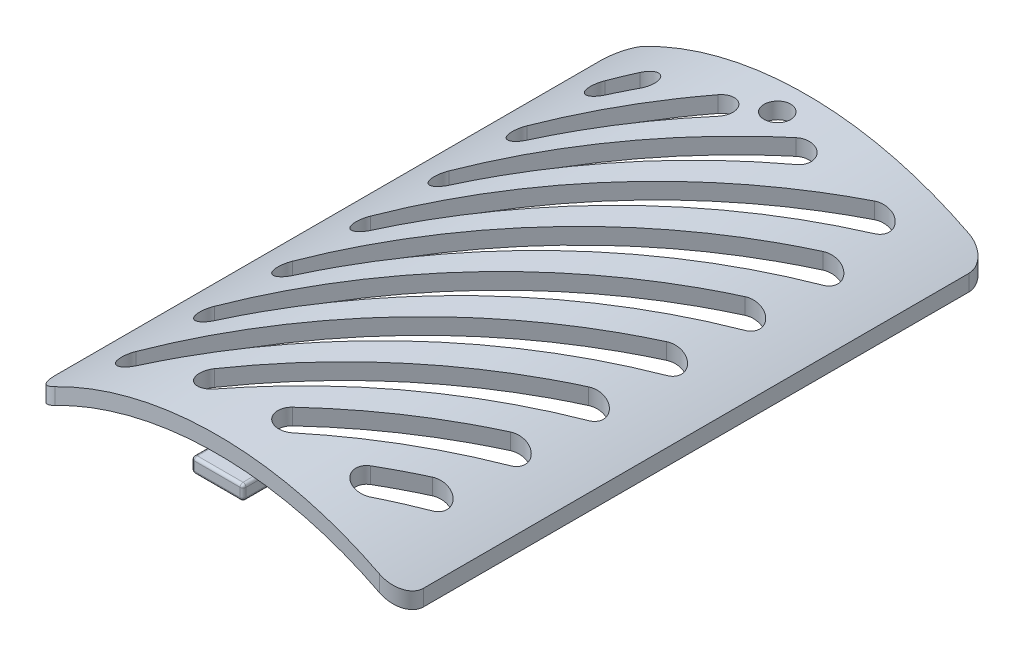
SolidWorks part; units mm, degrees
ref_plane "Plan de face" through (0, 0, 0) normal (0, 0, 1) x (1, 0, 0)
ref_plane "Plan de dessus" through (0, 0, 0) normal (0, 1, 0) x (1, 0, 0)
ref_plane "Plan de droite" through (0, 0, 0) normal (1, 0, 0) x (0, 0, -1)
sketch "Esquisse2" plane through (0, 0, 0) normal (0, 0, 1) x (1, 0, 0)
  line L1 (-25, 0) -> (25, 0) construction
  line L2 (-25, 0) -> (-25, 2.2)
  line L3 (25, 0) -> (25, 2.2)
  line L4 (0, 9.2) -> (0, 7) construction
  arc A0 (-25, 0) -> (25, 0) centre (0, -41.1429) cw
  arc A1 (-25, 2.2) -> (25, 2.2) centre (0, -38.9429) cw
  point P4 (0, 0)
  point P6 (0, 7)
  dimension "D1" = 50
  dimension "D2" = 7
  dimension "D3" = 2.2
extrude "Boss.-Extru.1" add sketch "Esquisse2" along normal blind 80
sketch "Esquisse3" plane through (0, 0, 0) normal (1, 0, 0) x (0, 0, -1)
  line L0 (-77.9, 7) -> (-77.9, 5)
  line L2 (-77.9, 5) -> (-80, 5)
  line L3 (-80, 5) -> (-80, 3)
  line L6 (-73.9, 7) -> (-77.9, 7)
  line L7 (-77.9, 7) -> (-77.9, 9.2) construction
  line L8 (-80, 3) -> (-75.9, 3)
  line L9 (-75.9, 3) -> (-73.9, 5)
  line L10 (-73.9, 5) -> (-73.9, 7)
  line L11 (-77.9, 9.2) -> (-80, 9.2) construction
  dimension "D1" = 2.1
  dimension "D2" = 2
  dimension "D3" = 4
  dimension "D4" = 2
  dimension "D5" = 2.2
  dimension "D6" = 135
  dimension "D7" = 2.1
extrude "Boss.-Extru.2" add sketch "Esquisse3" along normal mid plane 7
ref_plane "Plan1" through (0, 9.2, 0) normal (0, 1, 0) x (1, 0, 0)
hole_wizard "Dégagement M31" positions "Esquisse7" profile "Esquisse8" hole size "M3" standard "ISO"
sketch "Esquisse7" plane through (0, 9.2, 0) normal (0, 1, 0) x (1, 0, 0)
  line L0 (25, 0) -> (-25, 0) construction
  line L1 (0, -4) -> (0, 0) construction
  point P0 (0, -4)
  dimension "D1" = 4
sketch "Esquisse8" plane through (0, 9.2, 4) normal (1, 0, 0) x (0, 0, 1)
  line L0 (0, 0) -> (0, 11.0815)
  line L1 (0, 11.0815) -> (1.8, 10)
  line L2 (1.8, 10) -> (1.8, 0)
  line L5 (1.8, 0) -> (0, 0)
  line L10 (0, 11.0815) -> (-1.8, 10) construction
  line L11 (0, -6.35) -> (0, 107.95) construction
  dimension "Diamètre du perçage" = 3.6
  dimension "Profondeur du perçage" = 10
  dimension "Angle de pointe" = 118
fillet "Congé1" radius 3 4 edges at (25, 1.1, 0) (25, 1.1, 80) (-25, 1.1, 0) (-25, 1.1, 80)
sketch "Esquisse9" plane through (0, 9.2, 0) normal (0, 1, 0) x (1, 0, 0)
  line L0 (-18, -73) -> (18, -37) construction
  line L1 (-19.4142, -71.5858) -> (16.5858, -35.5858)
  line L2 (-16.5858, -74.4142) -> (19.4142, -38.4142)
  line L3 (-18, -62.3934) -> (18, -26.3934) construction
  line L4 (-19.4142, -60.9792) -> (16.5858, -24.9792)
  line L5 (-16.5858, -63.8076) -> (19.4142, -27.8076)
  line L6 (-18, -51.7868) -> (18, -15.7868) construction
  line L7 (-19.4142, -50.3726) -> (16.5858, -14.3726)
  line L8 (-16.5858, -53.201) -> (19.4142, -17.201)
  line L9 (-18, -41.1802) -> (16.1802, -7) construction
  line L10 (-19.4142, -39.766) -> (14.766, -5.5858)
  line L11 (-16.5858, -42.5944) -> (17.5944, -8.4142)
  line L12 (-22, -80) -> (22, -80) construction
  line L13 (-25, -77) -> (-25, -3) construction
  line L14 (25, -77) -> (25, -3) construction
  line L15 (-7.3934, -73) -> (18, -47.6066) construction
  line L16 (-8.8076, -71.5858) -> (16.5858, -46.1924)
  line L17 (-5.9792, -74.4142) -> (19.4142, -49.0208)
  line L18 (3.2132, -73) -> (18, -58.2132) construction
  line L19 (1.799, -71.5858) -> (16.5858, -56.799)
  line L20 (4.6274, -74.4142) -> (19.4142, -59.6274)
  line L21 (13.8198, -73) -> (18, -68.8198) construction
  line L22 (12.4056, -71.5858) -> (16.5858, -67.4056)
  line L23 (15.234, -74.4142) -> (19.4142, -70.234)
  line L24 (-18, -30.5736) -> (5.5736, -7) construction
  line L25 (-19.4142, -29.1594) -> (4.1594, -5.5858)
  line L26 (-16.5858, -31.9878) -> (6.9878, -8.4142)
  line L27 (-18, -19.967) -> (-5.033, -7) construction
  line L28 (-19.4142, -18.5528) -> (-6.4472, -5.5858)
  line L29 (-16.5858, -21.3812) -> (-3.6188, -8.4142)
  line L30 (-18, -9.3604) -> (-15.6396, -7) construction
  line L31 (-19.4142, -7.9462) -> (-17.0538, -5.5858)
  line L32 (-16.5858, -10.7746) -> (-14.2254, -8.4142)
  line L33 (22, 0) -> (-22, 0) construction
  arc A0 (-19.4142, -71.5858) -> (-16.5858, -74.4142) centre (-18, -73) ccw
  arc A5 (19.4142, -38.4142) -> (16.5858, -35.5858) centre (18, -37) ccw
  arc A6 (-19.4142, -60.9792) -> (-16.5858, -63.8076) centre (-18, -62.3934) ccw
  arc A7 (19.4142, -27.8076) -> (16.5858, -24.9792) centre (18, -26.3934) ccw
  arc A8 (-19.4142, -50.3726) -> (-16.5858, -53.201) centre (-18, -51.7868) ccw
  arc A9 (19.4142, -17.201) -> (16.5858, -14.3726) centre (18, -15.7868) ccw
  arc A10 (-19.4142, -39.766) -> (-16.5858, -42.5944) centre (-18, -41.1802) ccw
  arc A11 (17.5944, -8.4142) -> (14.766, -5.5858) centre (16.1802, -7) ccw
  arc A12 (-8.8076, -71.5858) -> (-5.9792, -74.4142) centre (-7.3934, -73) ccw
  arc A13 (19.4142, -49.0208) -> (16.5858, -46.1924) centre (18, -47.6066) ccw
  arc A14 (1.799, -71.5858) -> (4.6274, -74.4142) centre (3.2132, -73) ccw
  arc A15 (19.4142, -59.6274) -> (16.5858, -56.799) centre (18, -58.2132) ccw
  arc A16 (12.4056, -71.5858) -> (15.234, -74.4142) centre (13.8198, -73) ccw
  arc A17 (19.4142, -70.234) -> (16.5858, -67.4056) centre (18, -68.8198) ccw
  arc A18 (-19.4142, -29.1594) -> (-16.5858, -31.9878) centre (-18, -30.5736) ccw
  arc A19 (6.9878, -8.4142) -> (4.1594, -5.5858) centre (5.5736, -7) ccw
  arc A20 (-19.4142, -18.5528) -> (-16.5858, -21.3812) centre (-18, -19.967) ccw
  arc A21 (-3.6188, -8.4142) -> (-6.4472, -5.5858) centre (-5.033, -7) ccw
  arc A22 (-19.4142, -7.9462) -> (-16.5858, -10.7746) centre (-18, -9.3604) ccw
  arc A23 (-14.2254, -8.4142) -> (-17.0538, -5.5858) centre (-15.6396, -7) ccw
  point P2 (0, -55)
  point P7 (0, -44.3934)
  point P14 (0, -33.7868)
  point P21 (-0.9099, -24.0901)
  point P28 (5.3033, -60.3033)
  point P41 (10.6066, -65.6066)
  point P48 (15.9099, -70.9099)
  point P55 (-6.2132, -18.7868)
  point P62 (-11.5165, -13.4835)
  point P69 (-16.8198, -8.1802)
  point P76 (-3.2132, -5.1802)
  dimension "D1" = 2
  dimension "D2" = 7
  dimension "D3" = 7
  dimension "D4" = 7
  dimension "D5" = 45
  dimension "D6" = 7.5
  dimension "D7" = 7.5
  dimension "D8" = 7.5
  dimension "D9" = 7.5
  dimension "D10" = 7.5
  dimension "D11" = 7.5
  dimension "D12" = 7.5
  dimension "D13" = 7.5
  dimension "D14" = 7.5
  dimension "D15" = 7
extrude "Enlèv. mat.-Extru.1" cut sketch "Esquisse9" against normal through all
fillet "Congé2" radius 0.4 8 edges at (3.5, 5, 78.95) (3.5, 3, 77.95) (-3.5, 5, 78.95) (-3.5, 3, 77.95) (0, 5, 80) (3.5, 4, 80) (0, 3, 80) (-3.5, 4, 80)
